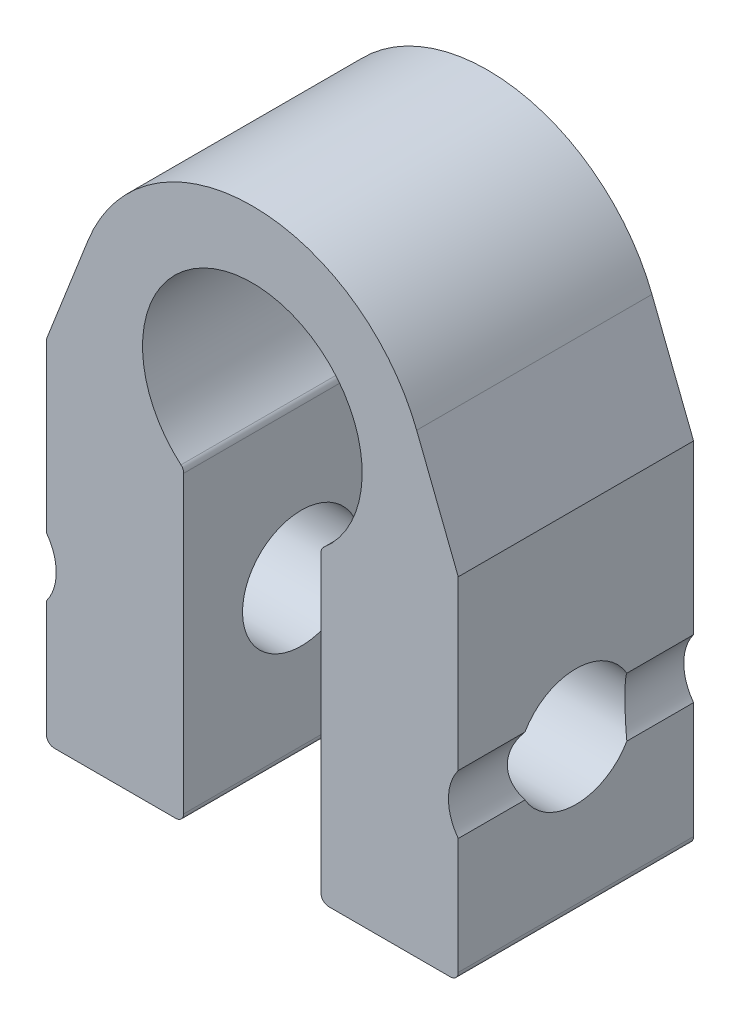
SolidWorks part; units mm, degrees
ref_plane "正面" through (0, 0, 0) normal (0, 0, 1) x (1, 0, 0)
ref_plane "平面" through (0, 0, 0) normal (0, 1, 0) x (1, 0, 0)
ref_plane "右側面" through (0, 0, 0) normal (1, 0, 0) x (0, 0, -1)
sketch "ｽｹｯﾁ1" plane through (0, 0, 0) normal (0, 0, 1) x (1, 0, 0)
  line L0 (-4.19, 1.6413) -> (-8.75, -10) construction
  line L1 (-8.75, -10) -> (-1.75, -10) construction
  line L3 (0, 0) -> (0, -10.4059) construction
  line L4 (4.19, 1.6413) -> (8.75, -10) construction
  line L5 (8.75, -10) -> (1.75, -10) construction
  line L8 (-5.25, -10) -> (-5.25, -1.0648)
  line L10 (5.25, -10) -> (5.25, -1.0648)
  line L11 (-5.25, -10) -> (-1.75, -10)
  line L12 (1.75, -10) -> (5.25, -10)
  line L13 (-4.19, 1.6413) -> (-5.25, -1.0648)
  line L14 (5.25, -1.0648) -> (4.19, 1.6413)
  line L15 (-1.75, -2.1857) -> (-1.75, -10)
  line L16 (1.75, -2.1857) -> (1.75, -10)
  arc A0 (1.75, -2.1857) -> (-1.75, -2.1857) centre (0, 0) ccw
  arc A2 (4.19, 1.6413) -> (-4.19, 1.6413) centre (0, 0) ccw
  dimension "D1" = 5.6
  dimension "D2" = 4.5
  dimension "D3" = 1.75
  dimension "D4" = 10
  dimension "D5" = 7
extrude "ﾎﾞｽ - 押し出し1" add sketch "ｽｹｯﾁ1" along normal blind 6 contours A0 L15 L11 L8 L13 A2 L14 L10 L12 L16
sketch "ｽｹｯﾁ2" plane through (0, 0, 6) normal (0, 0, 1) x (1, 0, 0)
  line L0 (-1.75, -6.0929) -> (-6.25, -6.0929) construction
  line L2 (-5.25, -10) -> (-5.25, -1.0648) construction
  line L3 (-5.25, -6.8429) -> (-5.25, -5.3429)
  line L4 (-1.75, -10) -> (1.75, -10) construction
  line L5 (5.25, -6.8429) -> (5.25, -5.3429)
  line L6 (0, 0) -> (0, -10) construction
  line L7 (-1.75, -2.1857) -> (-1.75, -10) construction
  line L8 (-5.25, -10) -> (-1.75, -10) construction
  arc A0 (-5.25, -6.8429) -> (-5.25, -5.3429) centre (-6.25, -6.0929) ccw
  arc A1 (5.25, -6.8429) -> (5.25, -5.3429) centre (6.25, -6.0929) cw
  point P18 (0, 0)
  point P19 (-1.75, -6.0929)
  point P20 (0, 0)
  dimension "D1" = 1
  dimension "D2" = 2.5
extrude "ｶｯﾄ - 押し出し1" cut sketch "ｽｹｯﾁ2" against normal through all
sketch "ｽｹｯﾁ3" plane through (-5.25, 0, 0) normal (-1, 0, 0) x (0, 0, 1)
  line L0 (0, -6.0929) -> (6, -6.0929) construction
  line L1 (0, -5.3429) -> (0, -6.8429) construction
  line L2 (6, -6.8429) -> (6, -5.3429) construction
  circle A0 centre (3, -6.0929) radius 1.5
  dimension "D1" = 3
extrude "ｶｯﾄ - 押し出し3" cut sketch "ｽｹｯﾁ3" against normal through all
fillet "ﾌｨﾚｯﾄ1" radius 0.2 6 edges at (5.25, -10, 3) (-5.25, -10, 3) (1.75, -10, 3) (-1.75, -10, 3) (1.75, -2.1857, 3) (-1.75, -2.1857, 3)
